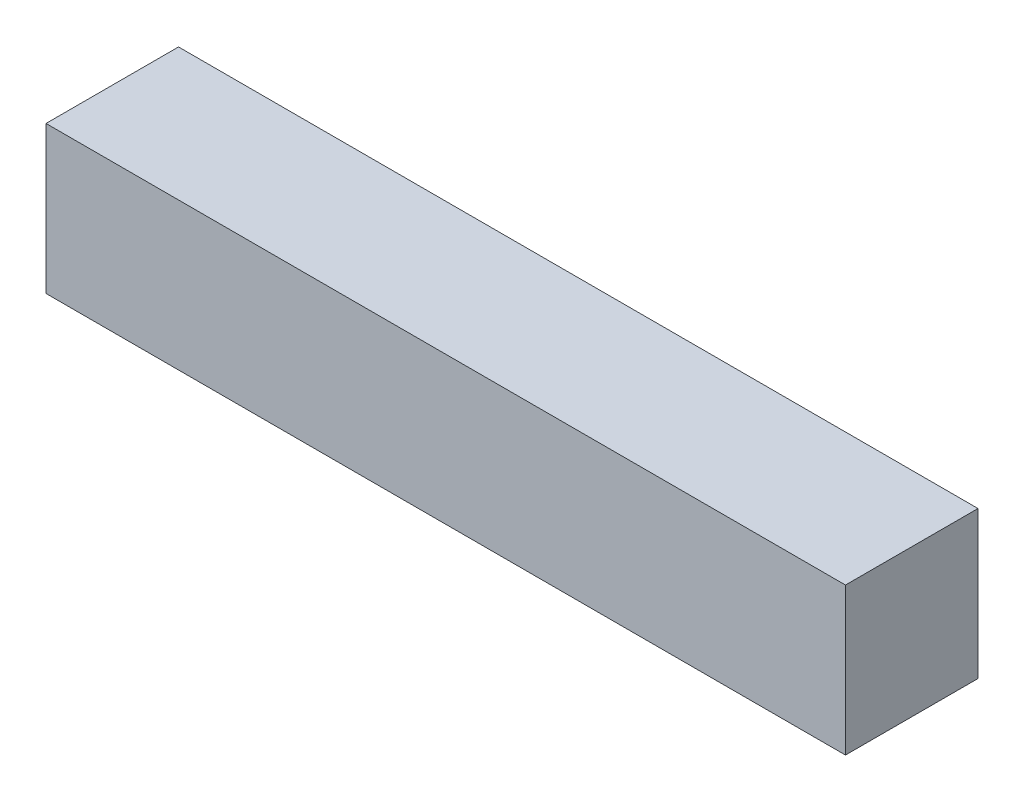
SolidWorks part; units mm, degrees
ref_plane "Ebene vorne" through (0, 0, 0) normal (0, 0, 1) x (1, 0, 0)
ref_plane "Ebene oben" through (0, 0, 0) normal (0, 1, 0) x (1, 0, 0)
ref_plane "Ebene rechts" through (0, 0, 0) normal (1, 0, 0) x (0, 0, -1)
sketch "Skizze1" plane through (0, 0, 0) normal (0, 0, 1) x (1, 0, 0)
  line L1 (-241.3, -44.45) -> (241.3, -44.45)
  line L2 (-241.3, -44.45) -> (-241.3, 44.45)
  line L3 (-241.3, 44.45) -> (241.3, 44.45)
  line L4 (241.3, -44.45) -> (241.3, 44.45)
  line L5 (-241.3, -44.45) -> (241.3, 44.45) construction
  line L6 (-241.3, 44.45) -> (241.3, -44.45) construction
  point P0 (0, 0)
  dimension "D1" = 88.9
  dimension "D2" = 482.6
extrude "Aufsatz-Linear austragen1" add sketch "Skizze1" against normal blind 80
